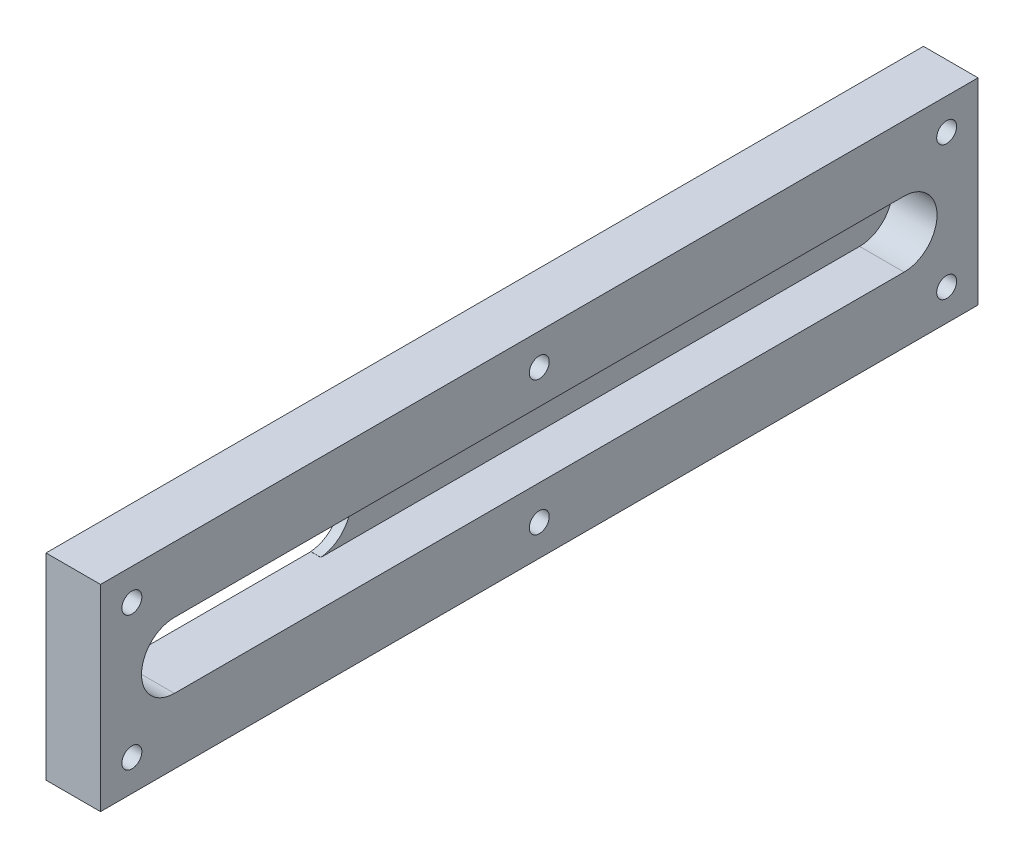
SolidWorks part; units mm, degrees
material "Delrin 2700 NC010, Low Viscosity Acetal Copolymer (SS)"
ref_plane "Front" through (0, 0, 0) normal (0, 0, 1) x (1, 0, 0)
ref_plane "Top" through (0, 0, 0) normal (0, 1, 0) x (1, 0, 0)
ref_plane "Right" through (0, 0, 0) normal (1, 0, 0) x (0, 0, -1)
sketch "Sketch1" plane through (0, 0, 0) normal (1, 0, 0) x (0, 0, -1)
  line L0 (-73.9253, 0) -> (73.9253, 0) construction
  line L1 (88.9, -19.939) -> (-88.9, -19.939)
  line L2 (88.9, -19.939) -> (88.9, 19.939)
  line L3 (88.9, 19.939) -> (-88.9, 19.939)
  line L4 (-88.9, -19.939) -> (-88.9, 19.939)
  line L5 (88.9, -19.939) -> (-88.9, 19.939) construction
  line L6 (88.9, 19.939) -> (-88.9, -19.939) construction
  line L7 (-73.9253, 6.6675) -> (73.9253, 6.6675)
  line L8 (-73.9253, -6.6675) -> (73.9253, -6.6675)
  arc A0 (-73.9253, 6.6675) -> (-73.9253, -6.6675) centre (-73.9253, 0) ccw
  arc A1 (73.9253, -6.6675) -> (73.9253, 6.6675) centre (73.9253, 0) ccw
  point P0 (0, 0)
  point P8 (0, 0)
  dimension "D4" = 13.335
  dimension "D1" = 147.8505
  dimension "D2" = 177.8
  dimension "D3" = 39.878
extrude "Boss-Extrude1" add sketch "Sketch1" along normal blind 11.049
hole_wizard "#10-32 Tapped Hole1" positions "Sketch3" profile "Sketch4" tap size "#10-32" standard "ANSI Inch" end condition through all
sketch "Sketch3" plane through (11.049, 0, 0) normal (1, 0, 0) x (0, 0, -1)
  line L0 (-82.55, 13.589) -> (0, 13.589) construction
  line L1 (0, 13.589) -> (82.55, 13.589) construction
  line L3 (-82.55, 19.939) -> (-82.55, 13.589) construction
  line L4 (88.9, 19.939) -> (-88.9, 19.939) construction
  line L5 (-82.55, 13.589) -> (-82.55, -13.589) construction
  line L6 (-82.55, -13.589) -> (-82.55, -19.939) construction
  line L7 (-88.9, -19.939) -> (88.9, -19.939) construction
  line L8 (-88.9, 19.939) -> (-88.9, -19.939) construction
  point P0 (-82.55, 13.589)
  point P2 (-82.55, -13.589)
  point P4 (0, -13.589)
  point P6 (82.55, -13.589)
  point P8 (82.55, 13.589)
  point P10 (0, 13.589)
  dimension "D1" = 6.35
  dimension "D2" = 6.35
sketch "Sketch4" plane through (11.049, 13.589, 82.55) normal (0, 1, 0) x (0, 0, -1)
  line L0 (0, 0) -> (0, 11.049)
  line L1 (0, 11.049) -> (2.0193, 11.049)
  line L2 (2.0193, 11.049) -> (2.0193, 0)
  line L5 (2.0193, 0) -> (0, 0)
  line L11 (0, -6.35) -> (0, 107.95) construction
  dimension "Thru Tap Drill Dia." = 4.0386
  dimension "Thru Tap Drill Depth" = 11.049
cosmetic thread "Hole Thread1" parameters "D2"=4.826
cosmetic thread "Hole Thread2" parameters "D2"=4.826
cosmetic thread "Hole Thread3" parameters "D2"=4.826
cosmetic thread "Hole Thread4" parameters "D2"=4.826
cosmetic thread "Hole Thread5" parameters "D2"=4.826
cosmetic thread "Hole Thread6" parameters "D2"=4.826
sketch "Sketch5" plane through (0, 0, 0) normal (-1, 0, 0) x (0, 0, 1)
  line L0 (35.2438, 6.6675) -> (35.2438, 6.6421)
  line L1 (35.2438, -6.6421) -> (35.2438, -6.6675)
  line L2 (-73.9253, -6.6675) -> (73.9253, -6.6675)
  line L3 (73.9253, 6.6675) -> (-73.9253, 6.6675)
  line L4 (-73.9253, -6.6675) -> (35.2438, -6.6675)
  line L5 (35.2438, 6.6675) -> (-73.9253, 6.6675)
  arc A0 (35.2438, 6.6421) -> (35.2438, -6.6421) centre (35.8253, 0) ccw
  arc A1 (73.9253, -6.6675) -> (73.9253, 6.6675) centre (73.9253, 0) ccw construction
  arc A2 (73.9253, -6.6675) -> (73.9253, 6.6675) centre (73.9253, 0) ccw
  arc A3 (-73.9253, 6.6675) -> (-73.9253, -6.6675) centre (-73.9253, 0) ccw
  arc A5 (-73.9253, 6.6675) -> (-73.9253, -6.6675) centre (-73.9253, 0) ccw
  dimension "D2" = 38.1
  dimension "D3" = 0.0254
  dimension "D1" = 0
extrude "Boss-Extrude2" add sketch "Sketch5" against normal blind 2.032
